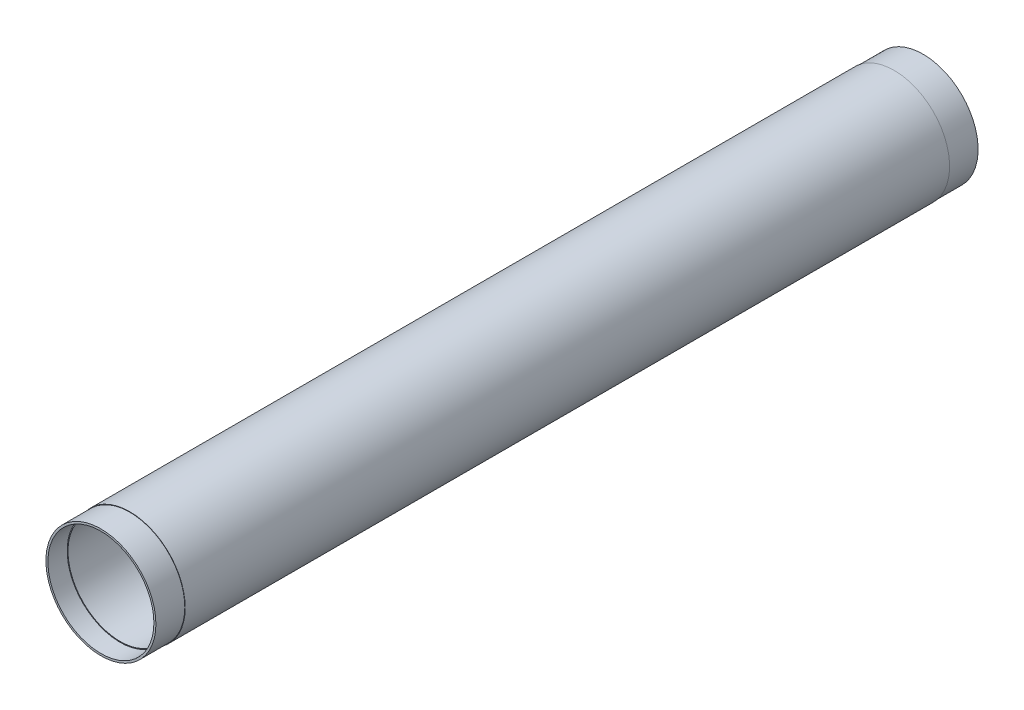
SolidWorks part; units mm, degrees
material "AISI 316 Stainless Steel Sheet (SS)"
ref_plane "Front Plane" through (0, 0, 0) normal (0, 0, 1) x (1, 0, 0)
ref_plane "Top Plane" through (0, 0, 0) normal (0, 1, 0) x (1, 0, 0)
ref_plane "Right Plane" through (0, 0, 0) normal (1, 0, 0) x (0, 0, -1)
sketch "Sketch1" plane through (0, 0, 0) normal (0, 0, 1) x (1, 0, 0)
  circle A0 centre (0, 0) radius 32.5
  circle A1 centre (0, 0) radius 34.5
  dimension "D1" = 2
  dimension "D2" = 69
extrude "Boss-Extrude1" add sketch "Sketch1" along normal blind 512
sketch "Sketch3" plane through (0, 0, 512) normal (0, 0, 1) x (1, 0, 0)
  circle A0 centre (0, 0) radius 33
  circle A1 centre (0, 0) radius 32.5
  circle A2 centre (0, 0) radius 32.5 construction
  dimension "D1" = 0.5
extrude "Cut-Extrude1" cut sketch "Sketch3" against normal blind 12
sketch "Sketch4" plane through (0, 0, 512) normal (0, 0, 1) x (1, 0, 0)
  circle A0 centre (0, 0) radius 34.5
  circle A1 centre (0, 0) radius 34.25
  circle A2 centre (0, 0) radius 34.5 construction
  dimension "D1" = 0.25
extrude "Cut-Extrude3" cut sketch "Sketch4" against normal blind 18
sketch "Sketch5" plane through (0, 0, 0) normal (0, 0, -1) x (-1, 0, 0)
  circle A0 centre (0, 0) radius 34.25
  circle A1 centre (0, 0) radius 34.5
  circle A2 centre (0, 0) radius 34.5 construction
  dimension "D1" = 0.25
extrude "Cut-Extrude4" cut sketch "Sketch5" against normal blind 18
sketch "Sketch6" plane through (0, 0, 0) normal (0, 1, 0) x (1, 0, 0)
  line L0 (0, 0) -> (0, -50000) construction
